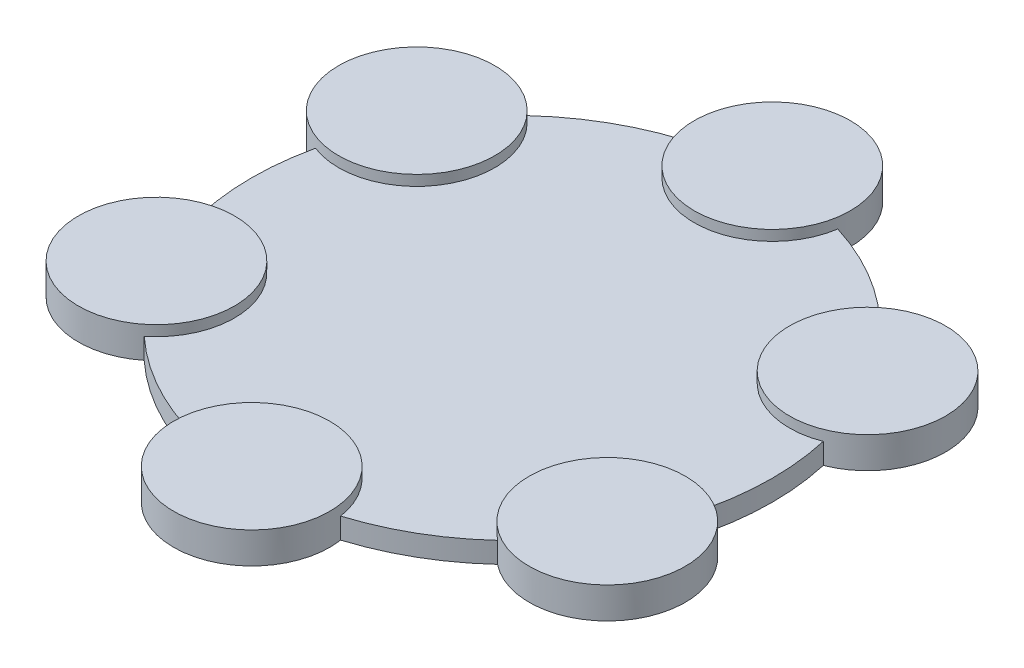
SolidWorks part; units mm, degrees
ref_plane "Front Plane" through (0, 0, 0) normal (0, 0, 1) x (1, 0, 0)
ref_plane "Top Plane" through (0, 0, 0) normal (0, 1, 0) x (1, 0, 0)
ref_plane "Right Plane" through (0, 0, 0) normal (1, 0, 0) x (0, 0, -1)
sketch "Esquisse2" plane through (0, 0, 0) normal (0, 1, 0) x (1, 0, 0)
  circle A0 centre (0, 0) radius 250
  dimension "D1" = 500
extrude "Boss.-Extru.2" add sketch "Esquisse2" along normal blind 20
sketch "Esquisse3" plane through (0, 0, 0) normal (0, -1, 0) x (1, 0, 0)
  line L1 (0, -0.9081) -> (0, 0.9081) construction
  circle A0 centre (0, 250) radius 75
  circle A1 centre (0, 0) radius 250 construction
  point P4 (-38.1276, 247.0755)
  dimension "D1" = 150
  dimension "D2" = 0
extrude "Boss.-Extru.3" add sketch "Esquisse3" against normal blind 30
pattern_circular "Répétition circulaire1" count 6 over 360 about axis through (0, 0, 0) along (0, 1, 0) of "Boss.-Extru.3"
